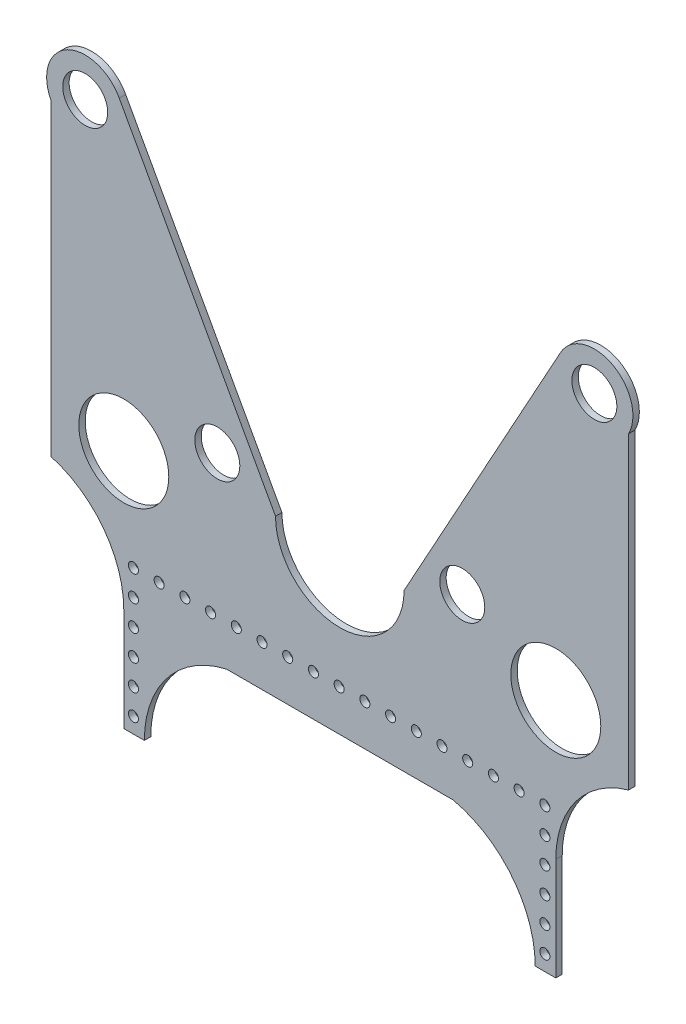
SolidWorks part; units mm, degrees
ref_plane "Front Plane" through (0, 0, 0) normal (0, 0, 1) x (1, 0, 0)
ref_plane "Top Plane" through (0, 0, 0) normal (0, 1, 0) x (1, 0, 0)
ref_plane "Right Plane" through (0, 0, 0) normal (1, 0, 0) x (0, 0, -1)
sketch "Sketch2" plane through (0, 0, 0) normal (0, 0, 1) x (1, 0, 0)
  line L0 (-106.68, -1085.9159) -> (-106.68, 48914.0841) construction
  line L1 (142.6324, 122.4629) -> (142.6324, -29.9371)
  line L2 (106.68, -1098.4025) -> (106.68, 48901.5975) construction
  line L3 (31.75, 0) -> (108.9183, 140.209)
  line L4 (0, -1082.0685) -> (0, 48917.9315) construction
  line L5 (-106.68, -44.45) -> (106.68, -44.45) construction
  line L6 (-106.68, -59.1767) -> (-106.68, -31.75)
  line L7 (0, -31.75) -> (106.68, -31.75) construction
  line L8 (106.68, -55.9582) -> (106.68, -31.75)
  line L9 (-31.75, 0) -> (-108.9183, 140.209)
  line L10 (31.75, 0) -> (108.9183, 140.209)
  line L11 (-106.68, -77.4976) -> (-106.68, -128.2976)
  line L12 (106.68, -77.4976) -> (106.68, -128.2976)
  line L13 (-106.68, -59.1767) -> (-106.68, -77.4976)
  line L14 (-55.88, -77.4976) -> (55.88, -77.4976)
  line L15 (106.68, -55.9582) -> (106.68, -77.4976)
  line L16 (-106.68, -77.4976) -> (-96.52, -77.4976) construction
  line L17 (-106.68, -77.4976) -> (-106.68, -128.2976)
  line L18 (-106.68, -128.2976) -> (-96.52, -128.2976)
  line L19 (-96.52, -77.4976) -> (-96.52, -128.2976)
  line L20 (106.68, -128.2976) -> (96.52, -128.2976)
  line L21 (55.88, -77.4976) -> (-55.88, -77.4976)
  line L22 (96.52, -77.4976) -> (96.52, -128.2976)
  line L23 (-106.68, -77.4976) -> (-96.52, -77.4976) construction
  line L24 (-96.52, -77.4976) -> (-106.68, -77.4976) construction
  line L25 (96.52, -77.4976) -> (106.68, -77.4976) construction
  line L26 (106.68, -77.4976) -> (96.52, -77.4976) construction
  line L27 (55.88, -77.4976) -> (96.52, -77.4976) construction
  line L28 (96.52, -77.4976) -> (55.88, -77.4976) construction
  line L29 (-96.52, -77.4976) -> (-55.88, -77.4976) construction
  line L30 (-55.88, -77.4976) -> (-96.52, -77.4976) construction
  line L33 (-106.68, -31.75) -> (0, -31.75) construction
  line L34 (-142.6324, 122.4629) -> (-142.6324, -29.9371)
  arc A0 (-31.75, 0) -> (31.75, 0) centre (0, 0) ccw
  arc A1 (-108.9183, 140.209) -> (-142.6324, 122.4629) centre (-125.7268, 131.2438) ccw
  circle A2 centre (-60.4845, 12.7) radius 11.1125
  arc A3 (31.75, 0) -> (0, 31.75) centre (0, 0) ccw construction
  arc A4 (0, 31.75) -> (-31.75, 0) centre (0, 0) ccw construction
  arc A5 (-96.52, -128.2976) -> (-55.88, -77.4976) centre (-44.45, -128.2976) cw
  arc A6 (96.52, -128.2976) -> (55.88, -77.4976) centre (44.45, -128.2976) ccw
  circle A7 centre (-125.7268, 131.2438) radius 11.1125
  circle A9 centre (-60.4845, 12.7) radius 19.05 construction
  circle A10 centre (60.4845, 12.7) radius 19.05 construction
  arc A11 (108.9183, 140.209) -> (142.6324, 122.4629) centre (125.7268, 131.2438) cw
  circle A12 centre (125.7268, 131.2438) radius 11.1125
  circle A34 centre (-101.9175, -57.15) radius 2.4892
  arc A40 (-142.6324, 122.4629) -> (-108.9183, 140.209) centre (-125.7268, 131.2438) ccw construction
  arc A41 (142.6324, 122.4629) -> (108.9183, 140.209) centre (125.7268, 131.2438) cw construction
  circle A42 centre (60.4845, 12.7) radius 11.1125
  circle A43 centre (-89.2175, -57.15) radius 2.4892
  circle A44 centre (-76.5175, -57.15) radius 2.4892
  circle A45 centre (-63.8175, -57.15) radius 2.4892
  circle A46 centre (-51.1175, -57.15) radius 2.4892
  circle A47 centre (-38.4175, -57.15) radius 2.4892
  circle A48 centre (-25.7175, -57.15) radius 2.4892
  circle A49 centre (-13.0175, -57.15) radius 2.4892
  circle A50 centre (-0.3175, -57.15) radius 2.4892
  circle A51 centre (12.3825, -57.15) radius 2.4892
  circle A52 centre (25.0825, -57.15) radius 2.4892
  circle A53 centre (37.7825, -57.15) radius 2.4892
  circle A54 centre (50.4825, -57.15) radius 2.4892
  circle A55 centre (63.1825, -57.15) radius 2.4892
  circle A56 centre (75.8825, -57.15) radius 2.4892
  circle A57 centre (88.5825, -57.15) radius 2.4892
  circle A58 centre (101.2825, -57.15) radius 2.4892
  circle A59 centre (-101.9175, -69.85) radius 2.4892
  circle A60 centre (-101.9175, -82.55) radius 2.4892
  circle A61 centre (-101.9175, -95.25) radius 2.4892
  circle A62 centre (-101.9175, -107.95) radius 2.4892
  circle A63 centre (-101.9175, -120.65) radius 2.4892
  circle A64 centre (101.2825, -69.85) radius 2.4892
  circle A65 centre (101.2825, -82.55) radius 2.4892
  circle A66 centre (101.2825, -95.25) radius 2.4892
  circle A67 centre (101.2825, -107.95) radius 2.4892
  circle A68 centre (101.2825, -120.65) radius 2.4892
  arc A69 (-106.68, -77.4976) -> (-142.6324, -29.9371) centre (-156.1145, -77.4976) ccw
  arc A70 (106.68, -77.4976) -> (142.6324, -29.9371) centre (156.1145, -77.4976) cw
  circle A71 centre (-106.68, -9.525) radius 22.225
  circle A72 centre (106.68, -9.525) radius 22.225
  point P89 (-106.68, -12.9035)
  point P101 (0, 0)
  point P109 (0, 0)
  dimension "D7" = 12.7
  dimension "D8" = 4.7625
  dimension "D9" = 25.4
  dimension "D3" = 44.45
  dimension "D14" = 106.68
  dimension "D17" = 38.1
  dimension "D5" = 52.07
  dimension "D15" = 31.75
  dimension "D16" = 22.225
  dimension "D18" = 22.225
  dimension "D19" = 19.05
  dimension "D23" = 4.9784
  dimension "D24" = 49.4345
  dimension "D21" = 125.7268
  dimension "D27" = 44.45
  dimension "D1" = 28.828
  dimension "D4" = 45.7476
  dimension "D6" = 88.9
  dimension "D10" = 17
  dimension "D11" = 12.7
  dimension "D12" = 12.7
  dimension "D13" = 111.76
  dimension "D20" = 142.6324
  dimension "D22" = 6
  dimension "D25" = 152.4
  dimension "D26" = 12.7
extrude "Boss-Extrude1" add sketch "Sketch2" along normal blind 3.175
